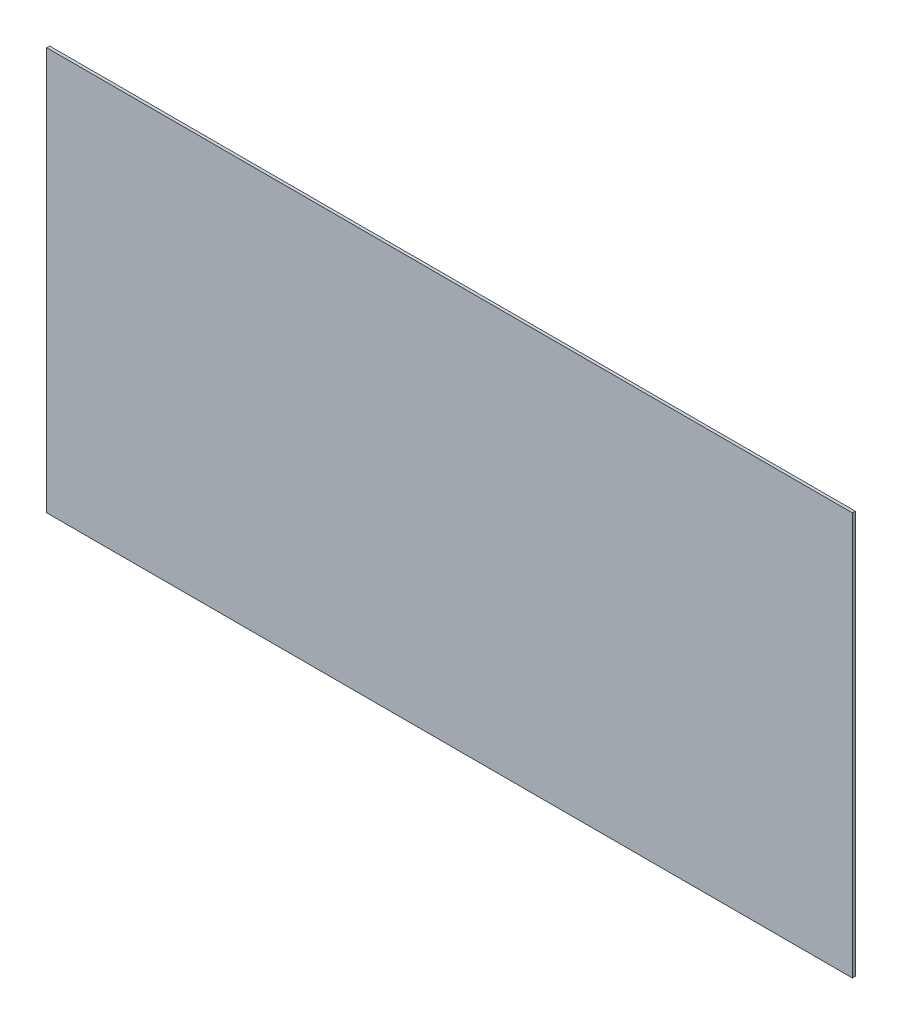
SolidWorks part; units mm, degrees
ref_plane "Спереди" through (0, 0, 0) normal (0, 0, 1) x (1, 0, 0)
ref_plane "Сверху" through (0, 0, 0) normal (0, 1, 0) x (1, 0, 0)
ref_plane "Справа" through (0, 0, 0) normal (1, 0, 0) x (0, 0, -1)
sketch "Эскиз1" plane through (0, 0, 0) normal (0, 0, 1) x (1, 0, 0)
  line L1 (-2453.5789, 1225.4928) -> (46.4211, 1225.4928)
  line L2 (-2453.5789, 1225.4928) -> (-2453.5789, -24.5072)
  line L3 (-2453.5789, -24.5072) -> (46.4211, -24.5072)
  line L4 (46.4211, 1225.4928) -> (46.4211, -24.5072)
  line L5 (-2453.5789, 1225.4928) -> (46.4211, -24.5072) construction
  line L6 (-2453.5789, -24.5072) -> (46.4211, 1225.4928) construction
  point P0 (-1203.5789, 600.4928)
extrude "Бобышка-Вытянуть1" add sketch "Эскиз1" along normal blind 9
